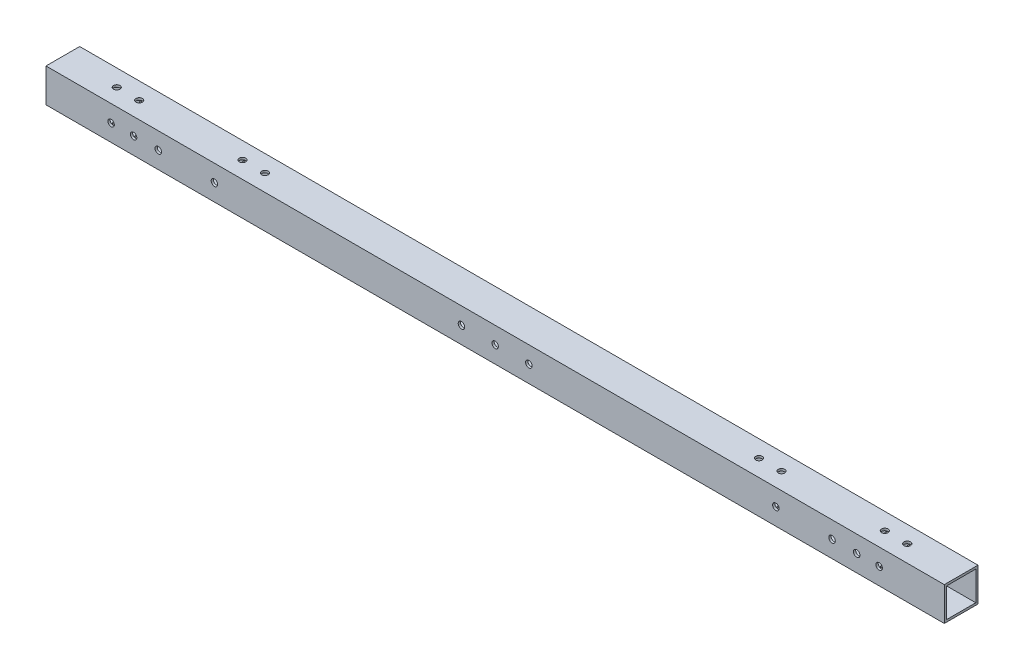
SolidWorks part; units mm, degrees
material "Thornel Mat VMA"
ref_plane "前视基准面" through (0, 0, 0) normal (0, 0, 1) x (1, 0, 0)
ref_plane "上视基准面" through (0, 0, 0) normal (0, 1, 0) x (1, 0, 0)
ref_plane "右视基准面" through (0, 0, 0) normal (1, 0, 0) x (0, 0, -1)
other "Configuration Table"
sketch "草图1" plane through (0, 0, 0) normal (1, 0, 0) x (0, 0, -1)
  line L0 (-6.5, -6.5) -> (-6.5, 6.5)
  line L1 (-7.5, -7.5) -> (7.5, -7.5)
  line L2 (-7.5, -7.5) -> (-7.5, 7.5)
  line L3 (-7.5, 7.5) -> (7.5, 7.5)
  line L4 (7.5, -7.5) -> (7.5, 7.5)
  line L5 (-7.5, -7.5) -> (7.5, 7.5) construction
  line L6 (-7.5, 7.5) -> (7.5, -7.5) construction
  line L7 (-6.5, 6.5) -> (6.5, 6.5)
  line L8 (6.5, -6.5) -> (6.5, 6.5)
  line L9 (-6.5, -6.5) -> (6.5, -6.5)
  point P0 (0, 0)
  dimension "D1" = 15
  dimension "D2" = 15
  dimension "D3" = 1
extrude "凸台-拉伸1" add sketch "草图1" along normal blind 400
sketch "草图2" plane through (0, 0, 7.5) normal (0, 0, 1) x (1, 0, 0)
  circle A0 centre (371, 0) radius 1.45 construction
  circle A1 centre (361, 0) radius 1.45 construction
  circle A2 centre (350, 0) radius 1.45 construction
  circle A3 centre (325, 0) radius 1.45 construction
  circle A4 centre (215, 0) radius 1.45 construction
  circle A5 centre (200, 0) radius 1.45 construction
  circle A6 centre (185, 0) radius 1.45 construction
  circle A7 centre (75, 0) radius 1.45 construction
  circle A8 centre (50, 0) radius 1.45 construction
  circle A9 centre (39, 0) radius 1.45 construction
  circle A10 centre (29, 0) radius 1.45 construction
  circle A11 centre (371, 0) radius 1.45
  circle A12 centre (361, 0) radius 1.45
  circle A13 centre (350, 0) radius 1.45
  circle A14 centre (325, 0) radius 1.45
  circle A15 centre (215, 0) radius 1.45
  circle A16 centre (200, 0) radius 1.45
  circle A17 centre (185, 0) radius 1.45
  circle A18 centre (75, 0) radius 1.45
  circle A19 centre (50, 0) radius 1.45
  circle A20 centre (39, 0) radius 1.45
  circle A21 centre (29, 0) radius 1.45
extrude "切除-拉伸1" cut sketch "草图2" against normal through all
sketch "草图3" plane through (0, 7.5, 0) normal (0, 1, 0) x (1, 0, 0)
  circle A0 centre (376, 0) radius 1.45 construction
  circle A1 centre (366, 0) radius 1.45 construction
  circle A2 centre (320, 0) radius 1.45 construction
  circle A3 centre (310, 0) radius 1.45 construction
  circle A4 centre (90, 0) radius 1.45 construction
  circle A5 centre (80, 0) radius 1.45 construction
  circle A6 centre (34, 0) radius 1.45 construction
  circle A7 centre (24, 0) radius 1.45 construction
  circle A8 centre (376, 0) radius 1.45
  circle A9 centre (366, 0) radius 1.45
  circle A10 centre (320, 0) radius 1.45
  circle A11 centre (310, 0) radius 1.45
  circle A12 centre (90, 0) radius 1.45
  circle A13 centre (80, 0) radius 1.45
  circle A14 centre (34, 0) radius 1.45
  circle A15 centre (24, 0) radius 1.45
extrude "切除-拉伸2" cut sketch "草图3" against normal through all
